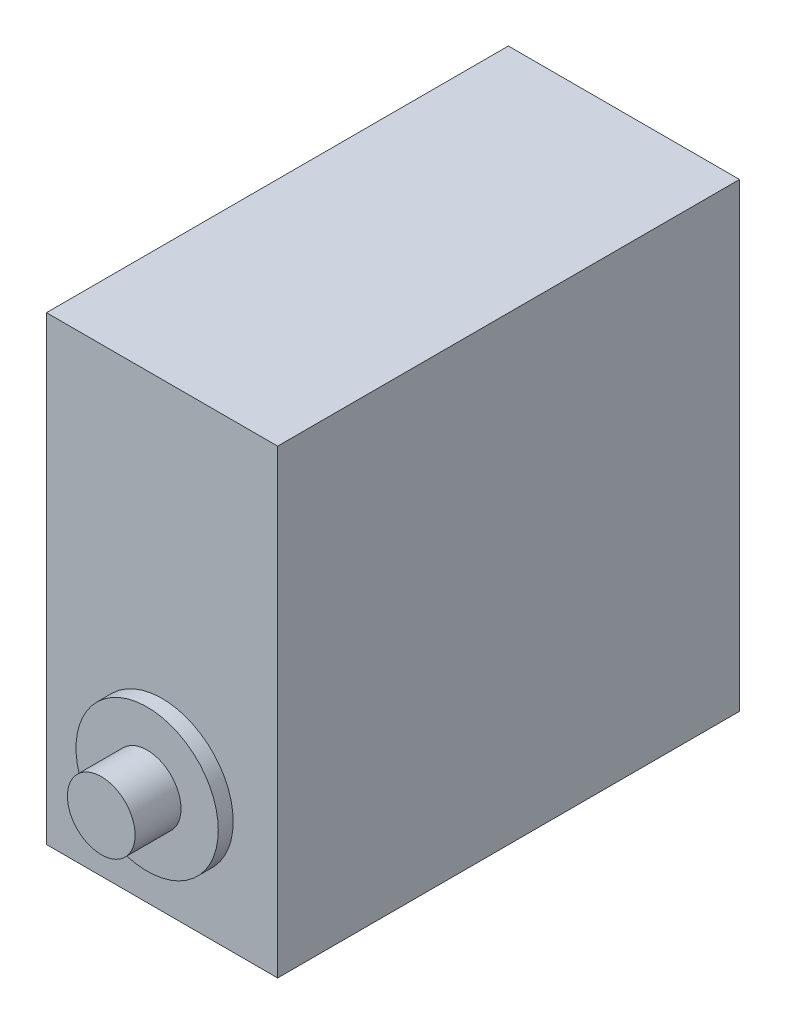
SolidWorks part; units mm, degrees
ref_plane "Front Plane" through (0, 0, 0) normal (1, 0, 0) x (0, 1, 0)
ref_plane "Top Plane" through (0, 0, 0) normal (0, 0, 1) x (0, 1, 0)
ref_plane "Right Plane" through (0, 0, 0) normal (0, 1, 0) x (-1, 0, 0)
sketch "Sketch1" plane through (0, 0, 0) normal (0, 0, 1) x (0, 1, 0)
  line L1 (-20.075, -10.075) -> (20.075, -10.075)
  line L2 (-20.075, -10.075) -> (-20.075, 10.075)
  line L3 (-20.075, 10.075) -> (20.075, 10.075)
  line L4 (20.075, -10.075) -> (20.075, 10.075)
  line L5 (-20.075, -10.075) -> (20.075, 10.075) construction
  line L6 (-20.075, 10.075) -> (20.075, -10.075) construction
  point P0 (0, 0)
  dimension "D1" = 40.15
  dimension "D2" = 20.15
extrude "Boss-Extrude1" add sketch "Sketch1" along normal mid plane 40.26
sketch "Sketch2" plane through (0, 0, 20.13) normal (0, 0, 1) x (1, 0, 0)
  line L1 (-10.075, -20.075) -> (10.075, -20.075) construction
  circle A0 centre (0, -10.205) radius 6.2
  point P2 (0, 296.9642)
  point P3 (0, -12.7099)
  point P5 (0, 0)
  dimension "D1" = 12.4
  dimension "D2" = 3.67
extrude "Boss-Extrude2" add sketch "Sketch2" along normal blind 1.3
mirror "Mirror1" about plane through (0, 0, 0) normal (0, 0, 1) of "Boss-Extrude2"
sketch "Sketch3" plane through (0, 0, -21.43) normal (0, 0, -1) x (1, 0, 0)
  circle A0 centre (0, 10.205) radius 3
  dimension "D1" = 6
extrude "Boss-Extrude3" add sketch "Sketch3" along normal blind 4
sketch "Sketch7" plane through (0, 0, 21.43) normal (0, 0, 1) x (1, 0, 0)
  circle A0 centre (0, -10.205) radius 2.95
  dimension "D1" = 5.9
extrude "Boss-Extrude4" add sketch "Sketch7" along normal blind 4
